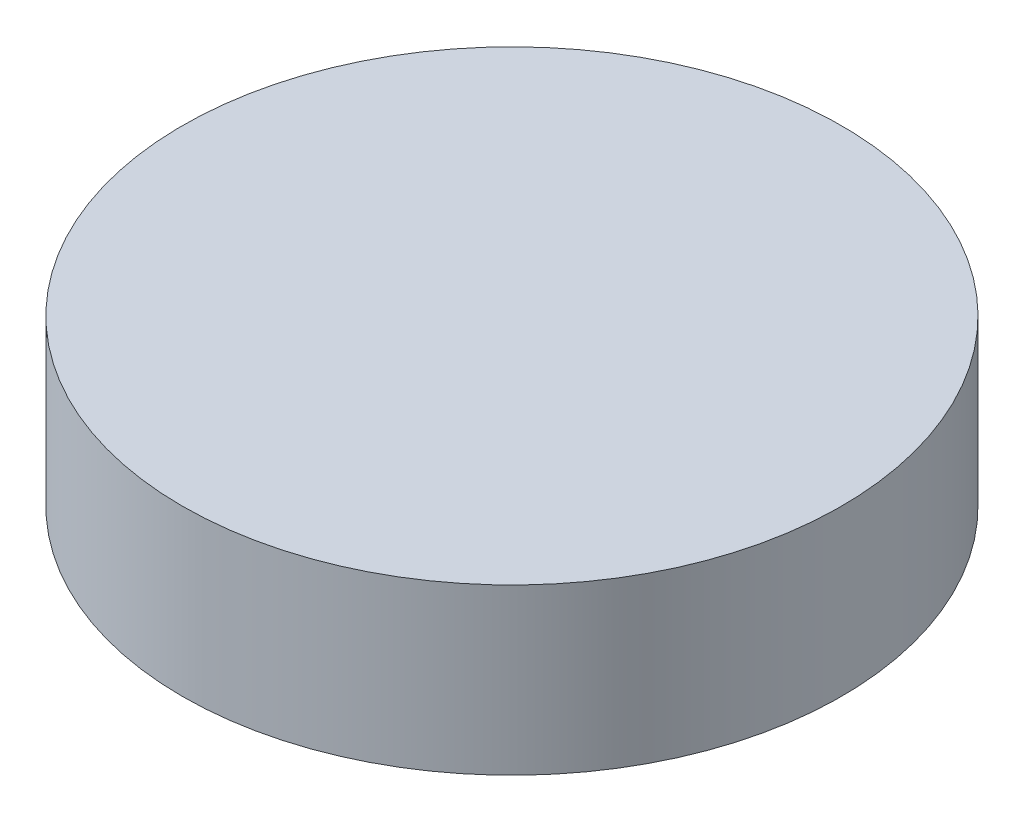
SolidWorks part; units mm, degrees
ref_plane "Front Plane" through (0, 0, 0) normal (0, 0, 1) x (1, 0, 0)
ref_plane "Top Plane" through (0, 0, 0) normal (0, 1, 0) x (1, 0, 0)
ref_plane "Right Plane" through (0, 0, 0) normal (1, 0, 0) x (0, 0, -1)
sketch "Sketch1" plane through (0, 0, 0) normal (0, 1, 0) x (1, 0, 0)
  circle A0 centre (0, 0) radius 127
  dimension "D1" = 254
extrude "Boss-Extrude1" add sketch "Sketch1" along normal blind 63.5
